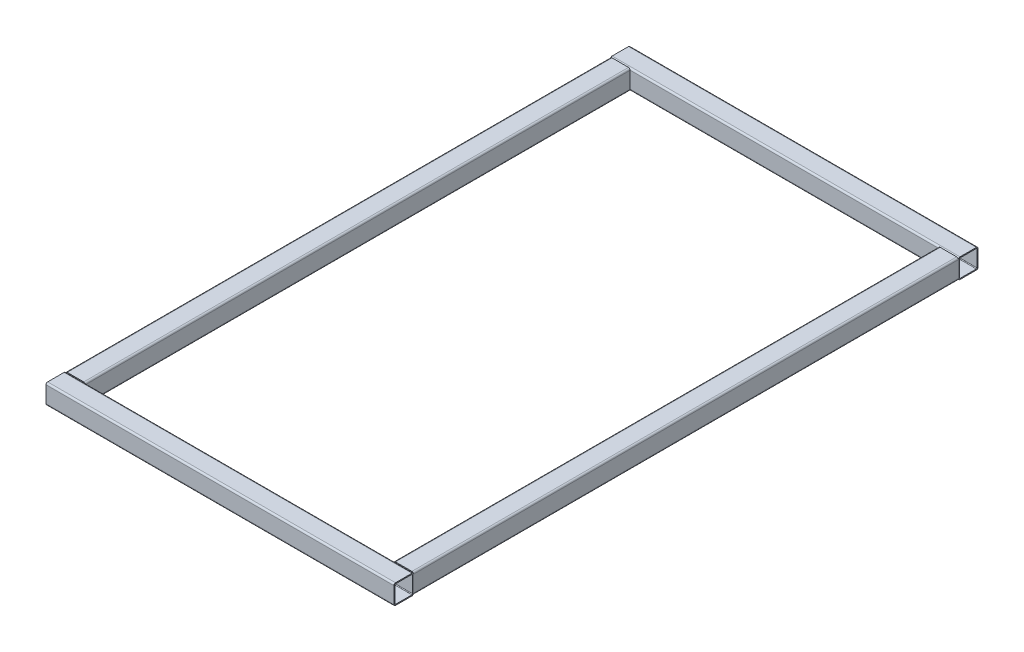
SolidWorks part; units mm, degrees
material "Ст 3 ГОСТ 380-88"
ref_plane "Спереди" through (0, 0, 0) normal (0, 0, 1) x (1, 0, 0)
ref_plane "Сверху" through (0, 0, 0) normal (0, 1, 0) x (1, 0, 0)
ref_plane "Справа" through (0, 0, 0) normal (1, 0, 0) x (0, 0, -1)
sketch "Эскиз1" plane through (0, 0, 0) normal (0, 0, 1) x (1, 0, 0)
  line L1 (500, -448) -> (-500, -448)
  line L2 (500, -448) -> (500, 448)
  line L3 (500, 448) -> (-500, 448)
  line L4 (-500, -448) -> (-500, 448)
  line L5 (500, -448) -> (-500, 448) construction
  line L6 (500, 448) -> (-500, -448) construction
  point P0 (0, 0)
  dimension "D1" = 1000
  dimension "D2" = 896
ref_plane "Плоскость1" through (0, 0, 1720) normal (0, 0, 1) x (1, 0, 0)
sketch "Эскиз2" plane through (0, 0, 1720) normal (0, 0, 1) x (1, 0, 0)
  line L4 (-500, -448) -> (500, -448)
  line L5 (-500, 448) -> (-500, -448)
  line L6 (500, 448) -> (-500, 448)
  line L7 (500, -448) -> (500, 448)
  line L8 (-500, -448) -> (500, -448)
  line L9 (-500, 448) -> (-500, -448)
  line L10 (500, 448) -> (-500, 448)
  line L11 (500, -448) -> (500, 448)
  dimension "D1" = 0
sketch3d "Трехмерный эскиз2"
  line L0 (500, 448, 0) -> (500, 448, 1720)
  line L1 (-500, 448, 0) -> (-500, 448, 1720)
  line L2 (500, -448, 0) -> (500, -448, 1720) construction
  line L3 (-500, -448, 0) -> (-500, -448, 1720) construction
  line L4 (500, 448, 860) -> (-500, 448, 860) construction
other "Прямоугольная труба 120 X 80 X 8(1)"
ref_plane "Плоскость2" through (500, 448, 1720) normal (-1, 0, 0) x (0, -1, 0)
sketch "Sketch1" plane through (500, 448, 1720) normal (-1, 0, 0) x (0, -1, 0)
  line L0 (-25, -27) -> (25, -27)
  line L1 (-27, -25) -> (-27, 25)
  line L2 (25, 27) -> (-25, 27)
  line L3 (27, 25) -> (27, -25)
  line L4 (-25, -30) -> (25, -30)
  line L5 (-30, -25) -> (-30, 25)
  line L6 (25, 30) -> (-25, 30)
  line L7 (30, 25) -> (30, -25)
  arc A0 (30, 25) -> (25, 30) centre (25, 25) ccw
  arc A1 (25, -30) -> (30, -25) centre (25, -25) ccw
  arc A2 (-30, -25) -> (-25, -30) centre (-25, -25) ccw
  arc A3 (-25, 30) -> (-30, 25) centre (-25, 25) ccw
  arc A4 (-25, 27) -> (-27, 25) centre (-25, 25) ccw
  arc A5 (27, 25) -> (25, 27) centre (25, 25) ccw
  arc A6 (25, -27) -> (27, -25) centre (25, -25) ccw
  arc A7 (-27, -25) -> (-25, -27) centre (-25, -25) ccw
  point P0 (0, 30)
  point P1 (30, 0)
  point P2 (0, -30)
  point P3 (-30, 0)
  point P4 (-30, 30)
  point P5 (30, 30)
  point P6 (30, -30)
  point P7 (-30, -30)
  point P8 (0, 0)
  point P33 (0, 0)
  dimension "D1" = 5
  dimension "Thickness" = 3
  dimension "V_leg" = 60
  dimension "H_leg" = 60
ref_plane "Плоскость3" through (0, 448, 0) normal (0, 1, 0) x (1, 0, 0)
ref_plane "Plane1" through (0, 0, 860) normal (0, 0, 1) x (1, 0, 0)
